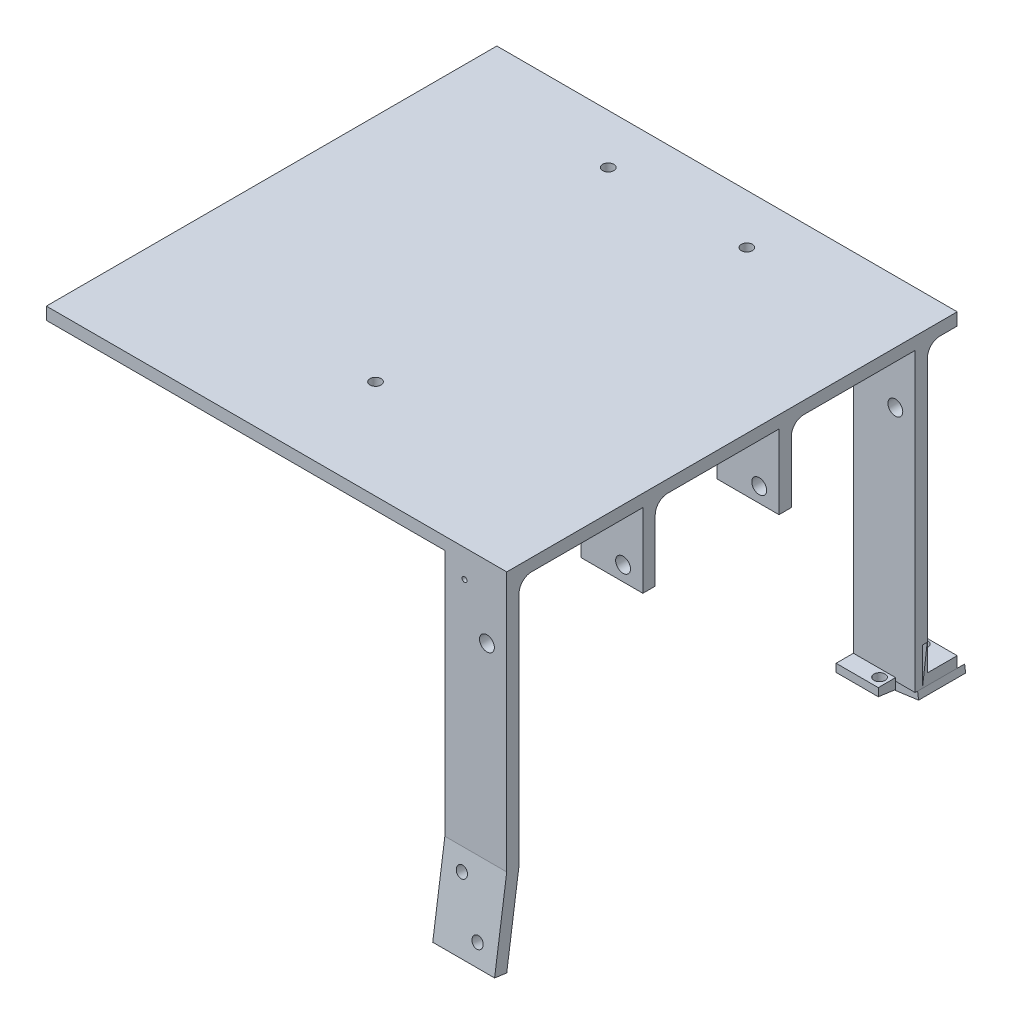
SolidWorks part; units mm, degrees
ref_plane "Front Plane" through (0, 0, 0) normal (0, 0, 1) x (1, 0, 0)
ref_plane "Top Plane" through (0, 0, 0) normal (0, 1, 0) x (1, 0, 0)
ref_plane "Right Plane" through (0, 0, 0) normal (1, 0, 0) x (0, 0, -1)
sketch "Sketch1" plane through (0, 0, 0) normal (0, 1, 0) x (1, 0, 0)
  line L0 (0, 0) -> (0, -300)
  line L1 (0, -300) -> (186, -300)
  line L2 (186, -300) -> (186, 0)
  line L3 (186, 0) -> (176, 0)
  line L4 (176, 0) -> (151, 0)
  line L5 (151, 0) -> (151, -56.1159)
  line L6 (151, -56.1159) -> (35, -56.1159)
  line L7 (35, -56.1159) -> (35, 0)
  line L8 (35, 0) -> (10, 0)
  line L9 (10, 0) -> (0, 0)
  line L10 (93, -300) -> (93, -56.1159) construction
  point P9 (93, -56.1159)
  dimension "D1" = 300
  dimension "D2" = 10
  dimension "D3" = 186
  dimension "D5" = 10
  dimension "D6" = 35
extrude "Boss-Extrude1" add sketch "Sketch1" along normal blind 5
sketch "Sketch2" plane through (0, 0, 0) normal (0, -1, 0) x (1, 0, 0)
  line L1 (50.5, 94) -> (55.5, 94)
  line L2 (50.5, 94) -> (50.5, 71.5)
  line L3 (50.5, 71.5) -> (55.5, 71.5)
  line L4 (55.5, 94) -> (55.5, 71.5)
  line L6 (135.5, 94) -> (130.5, 94)
  line L7 (135.5, 94) -> (135.5, 71.5)
  line L8 (135.5, 71.5) -> (130.5, 71.5)
  line L9 (130.5, 94) -> (130.5, 71.5)
  line L10 (0, 300) -> (186, 300) construction
  line L11 (186, 300) -> (186, 0) construction
  line L12 (0, 0) -> (0, 300) construction
  dimension "D1" = 5
  dimension "D2" = 22.5
  dimension "D3" = 5
  dimension "D4" = 206
  dimension "D5" = 22.5
  dimension "D6" = 50.5
  dimension "D7" = 50.5
extrude "Boss-Extrude2" add sketch "Sketch2" along normal blind 38
sketch "Sketch5" plane through (0, 0, 0) normal (0, -1, 0) x (1, 0, 0)
  line L0 (186, 300) -> (186, 0) construction
  line L1 (186, 295) -> (161, 295)
  line L2 (186, 295) -> (186, 300)
  line L3 (186, 300) -> (161, 300)
  line L4 (161, 295) -> (161, 300)
  line L5 (0, 300) -> (186, 300) construction
  line L6 (186, 240) -> (161, 240)
  line L7 (186, 240) -> (186, 245)
  line L8 (186, 245) -> (161, 245)
  line L9 (161, 240) -> (161, 245)
  line L10 (186, 185) -> (161, 185)
  line L11 (186, 185) -> (186, 190)
  line L12 (186, 190) -> (161, 190)
  line L13 (161, 185) -> (161, 190)
  line L14 (186, 130) -> (161, 130)
  line L15 (186, 130) -> (186, 135)
  line L16 (186, 135) -> (161, 135)
  line L17 (161, 130) -> (161, 135)
  dimension "D1" = 5
  dimension "D2" = 5
  dimension "D3" = 5
  dimension "D4" = 5
  dimension "D5" = 50
  dimension "D6" = 50
  dimension "D7" = 50
  dimension "D8" = 25
extrude "Boss-Extrude3" add sketch "Sketch5" along normal blind 30
fillet "Fillet3" radius 5 4 edges at (173.5, 0, 130) (173.5, 0, 185) (173.5, 0, 240) (173.5, 0, 295)
sketch "Sketch6" plane through (0, 0, 300) normal (0, 0, 1) x (1, 0, 0)
  line L0 (186, -30) -> (161, -30) construction
  line L1 (186, 5) -> (186, -30) construction
  circle A0 centre (178, -24) radius 3
  dimension "D1" = 6
  dimension "D2" = 6
  dimension "D3" = 8
extrude "Cut-Extrude4" cut sketch "Sketch6" against normal blind 172
sketch "Sketch7" plane through (0, 0, 0) normal (0, -1, 0) x (1, 0, 0)
  line L0 (0, 0) -> (0, 300) construction
  line L1 (0, 22.5) -> (5, 22.5)
  line L2 (0, 22.5) -> (0, 0)
  line L3 (0, 0) -> (5, 0)
  line L4 (5, 22.5) -> (5, 0)
  line L5 (186, 125) -> (186, 0) construction
  line L6 (186, 22.5) -> (181, 22.5)
  line L7 (186, 22.5) -> (186, 0)
  line L8 (186, 0) -> (181, 0)
  line L9 (181, 22.5) -> (181, 0)
  line L10 (186, 0) -> (151, 0) construction
  dimension "D1" = 5
  dimension "D2" = 5
  dimension "D3" = 22.5
  dimension "D4" = 22.5
extrude "Boss-Extrude4" add sketch "Sketch7" along normal blind 51.5
sketch "Sketch3" plane through (186, 0, 0) normal (1, 0, 0) x (0, 0, -1)
  line L4 (-71.5, 0) -> (-94, 0)
  line L5 (-71.5, -38) -> (-71.5, 0)
  line L6 (-94, -38) -> (-71.5, -38)
  line L7 (-94, 0) -> (-94, -38)
  line L9 (-71.5, -38) -> (-71.5, 0)
  line L10 (-94, -38) -> (-71.5, -38)
  line L11 (-94, 0) -> (-94, -38)
  line L13 (-71.5, 0) -> (-94, 0)
  circle A0 centre (-74, -32.9) radius 1.3 construction
  circle A1 centre (-91.5, -32.9) radius 1.3 construction
  circle A2 centre (-74, -32.9) radius 1.3
  circle A3 centre (-91.5, -32.9) radius 1.3
  circle A4 centre (-20, -46.4) radius 1.3 construction
  circle A5 centre (-2.5, -46.4) radius 1.3 construction
  circle A6 centre (-20, -46.4) radius 1.3
  circle A7 centre (-2.5, -46.4) radius 1.3
  dimension "D1" = 0
extrude "Cut-Extrude2" cut sketch "Sketch3" against normal through all contours A3 | A2 | A6 | A7
sketch "Sketch9" plane through (0, 0, 0) normal (0, -1, 0) x (1, 0, 0)
  line L0 (35, 0) -> (5, 0) construction
  line L1 (35, 0) -> (151, 0)
  line L2 (35, 0) -> (35, 63.7796)
  line L3 (35, 63.7796) -> (151, 63.7796)
  line L4 (151, 0) -> (151, 63.7796)
  line L5 (35, 56.1159) -> (35, 0) construction
  line L6 (151, 0) -> (151, 56.1159) construction
extrude "Cut-Extrude6" cut sketch "Sketch9" against normal blind 10
sketch "Sketch10" plane through (0, -30, 0) normal (0, -1, 0) x (1, 0, 0)
  line L1 (186, 295) -> (161, 295)
  line L2 (186, 295) -> (186, 300)
  line L3 (186, 300) -> (161, 300)
  line L4 (161, 295) -> (161, 300)
  line L5 (161, 130) -> (186, 130)
  line L6 (161, 130) -> (161, 135)
  line L7 (161, 135) -> (186, 135)
  line L8 (186, 130) -> (186, 135)
extrude "Boss-Extrude5" add sketch "Sketch10" along normal blind 70
sketch "Sketch11" plane through (186, 0, 0) normal (1, 0, 0) x (0, 0, -1)
  line L0 (-300, -100) -> (-304.9019, -134.6439)
  line L1 (-304.9019, -134.6439) -> (-300, -135.3374)
  line L2 (-300, -135.3374) -> (-295, -100)
  line L3 (-300, -100) -> (-295, -100)
extrude "Boss-Extrude6" add sketch "Sketch11" against normal blind 25
sketch "Sketch12" plane through (0, -100, 0) normal (0, -1, 0) x (1, 0, 0)
  line L1 (161, 130) -> (186, 130)
  line L2 (161, 130) -> (161, 135)
  line L3 (161, 135) -> (186, 135)
  line L4 (186, 130) -> (186, 135)
extrude "Boss-Extrude7" add sketch "Sketch12" along normal blind 19.72
sketch "Sketch13" plane through (0, 0, 130) normal (0, 0, -1) x (-1, 0, 0)
  line L0 (-186, -115.3141) -> (-186, -119.72)
  line L1 (-186, -119.72) -> (-186, -5) construction
  line L2 (-186, -119.72) -> (-161, -123.1352)
  line L3 (-161, -123.1352) -> (-161, -115.3141)
  line L4 (-161, -115.3141) -> (-186, -115.3141)
  line L5 (-161, -119.72) -> (-161, -5) construction
  line L8 (-88.5025, -135.5903) -> (-182.3051, -122.7762) construction
extrude "Boss-Extrude8" add sketch "Sketch13" along normal blind 15 and the other way blind 4
sketch "Sketch14" plane through (19.4625, -142.4702, 0) normal (0.1354, -0.9908, 0) x (0.9908, 0.1354, 0)
  line L0 (186.3576, 115) -> (168.0843, 132.0374)
  line L1 (168.0843, 115) -> (142.8521, 115) construction
  line L2 (168.0843, 115) -> (168.0843, 134) construction
  line L3 (168.0843, 132.0374) -> (198.0152, 130.431)
  line L4 (198.0152, 130.431) -> (197.5151, 111.3666)
  line L5 (197.5151, 111.3666) -> (186.3576, 109.6075)
  line L6 (186.3576, 109.6075) -> (186.3576, 115)
extrude "Cut-Extrude7" cut sketch "Sketch14" against normal blind 15
sketch "Sketch15" plane through (0, 39.652, 280.2402) normal (0, 0.1401, 0.9901) x (1, 0, 0)
  line L1 (161, -141.043) -> (161, -176.032) construction
  line L2 (186, -141.043) -> (161, -141.043) construction
  line L3 (186, -141.043) -> (186, -176.032) construction
  line L4 (161, -176.032) -> (186, -176.032) construction
  circle A0 centre (178, -168.032) radius 2.25
  circle A1 centre (169, -149.043) radius 2.25
  dimension "D1" = 4.5
  dimension "D2" = 4.5
  dimension "D3" = 8
  dimension "D4" = 8
  dimension "D5" = 8
  dimension "D6" = 8
extrude "Cut-Extrude8" cut sketch "Sketch15" against normal blind 20
sketch "Sketch16" plane through (0, 0, 0) normal (0, -1, 0) x (1, 0, 0)
  line L1 (166, 272) -> (172, 272)
  line L2 (166, 272) -> (166, 275)
  line L3 (166, 275) -> (172, 275)
  line L4 (172, 272) -> (172, 275)
  line L5 (143.4, 272) -> (137.4, 272)
  line L6 (143.4, 272) -> (143.4, 275)
  line L7 (143.4, 275) -> (137.4, 275)
  line L8 (137.4, 272) -> (137.4, 275)
  line L9 (166, 217) -> (172, 217)
  line L10 (166, 217) -> (166, 220)
  line L11 (166, 220) -> (172, 220)
  line L12 (172, 217) -> (172, 220)
  line L13 (166, 162) -> (172, 162)
  line L14 (166, 162) -> (166, 165)
  line L15 (166, 165) -> (172, 165)
  line L16 (172, 162) -> (172, 165)
  line L17 (137.4, 217) -> (143.4, 217)
  line L18 (137.4, 217) -> (137.4, 220)
  line L19 (137.4, 220) -> (143.4, 220)
  line L20 (143.4, 217) -> (143.4, 220)
  line L21 (137.4, 162) -> (143.4, 162)
  line L22 (137.4, 162) -> (137.4, 165)
  line L23 (137.4, 165) -> (143.4, 165)
  line L24 (143.4, 162) -> (143.4, 165)
  line L25 (186, 180) -> (186, 135) construction
  line L28 (161, 295) -> (186, 295) construction
  line L29 (161, 240) -> (186, 240) construction
  line L30 (161, 185) -> (186, 185) construction
  dimension "D1" = 3
  dimension "D2" = 3
  dimension "D3" = 3
  dimension "D4" = 3
  dimension "D5" = 3
  dimension "D6" = 3
  dimension "D7" = 20
  dimension "D8" = 22.6
  dimension "D9" = 6
  dimension "D10" = 6
  dimension "D11" = 23
  dimension "D12" = 23
  dimension "D13" = 23
extrude "Boss-Extrude9" add sketch "Sketch16" along normal blind 12.4
sketch "Sketch17" plane through (0, 0, 162) normal (0, 0, -1) x (-1, 0, 0)
  arc A0 (-169.75, -6.8) -> (-169.75, -5.6) centre (-168.95, -6.2) ccw construction
  arc A1 (-169.75, -6.8) -> (-169.75, -5.6) centre (-168.95, -6.2) ccw
  circle A2 centre (-168.95, -6.2) radius 1
  circle A3 centre (-140.45, -6.2) radius 1
extrude "Cut-Extrude9" cut sketch "Sketch17" against normal through all contours A1 A2 | A3
sketch "Sketch27" plane through (19.4625, -142.4702, 0) normal (0.1354, -0.9908, 0) x (0.9908, 0.1354, 0)
  line L1 (142.8521, 115) -> (168.0843, 115)
  line L2 (142.8521, 115) -> (142.8521, 134)
  line L3 (142.8521, 134) -> (168.0843, 134)
  line L4 (168.0843, 115) -> (168.0843, 134)
extrude "Boss-Extrude11" add sketch "Sketch27" along normal blind 3
fillet "Fillet4" radius 5 6 edges at (140.4, 0, 275) (169, 0, 275) (140.4, 0, 220) (169, 0, 220) (140.4, 0, 165) (169, 0, 165)
sketch "Sketch18" plane through (0, -115.3141, 0) normal (0, 1, 0) x (1, 0, 0)
  circle A0 centre (174.8857, -120.9947) radius 2.25
  dimension "D1" = 4.5
extrude "Cut-Extrude10" cut sketch "Sketch18" against normal through all
sketch "Sketch19" plane through (0, 0, 0) normal (0, -1, 0) x (1, 0, 0)
  line L0 (42.3, 80.75) -> (39.8, 80.75) construction
  line L1 (39.8, 84.75) -> (39.8, 80.75) construction
  line L2 (42.3, 84.75) -> (42.3, 80.75) construction
  line L3 (39.8, 84.75) -> (42.3, 84.75) construction
  line L4 (42.3, 80.75) -> (39.8, 80.75) construction
  line L5 (39.8, 84.75) -> (39.8, 80.75) construction
  line L6 (42.3, 84.75) -> (42.3, 80.75) construction
  line L7 (39.8, 84.75) -> (42.3, 84.75) construction
  line L8 (143.7, 80.75) -> (143.7, 84.75) construction
  line L9 (143.7, 84.75) -> (146.2, 84.75) construction
  line L10 (146.2, 80.75) -> (146.2, 84.75) construction
  line L11 (146.2, 80.75) -> (143.7, 80.75) construction
  line L12 (143.7, 80.75) -> (143.7, 84.75) construction
  line L13 (143.7, 84.75) -> (146.2, 84.75) construction
  line L14 (146.2, 80.75) -> (146.2, 84.75) construction
  line L15 (146.2, 80.75) -> (143.7, 80.75) construction
  line L16 (43.3, 79.75) -> (38.8, 79.75)
  line L17 (38.8, 85.75) -> (38.8, 79.75)
  line L18 (38.8, 85.75) -> (43.3, 85.75)
  line L19 (43.3, 85.75) -> (43.3, 79.75)
  line L20 (142.7, 79.75) -> (142.7, 85.75)
  line L21 (142.7, 85.75) -> (147.2, 85.75)
  line L22 (147.2, 79.75) -> (147.2, 85.75)
  line L23 (147.2, 79.75) -> (142.7, 79.75)
  line L31 (151, 0) -> (181, 0)
  line L32 (181, 0) -> (181, 22.5)
  line L34 (186, 22.5) -> (186, 125)
  line L35 (186, 125) -> (161, 125)
  line L36 (161, 125) -> (161, 135)
  line L37 (161, 135) -> (186, 135)
  line L38 (186, 135) -> (186, 180)
  line L39 (186, 180) -> (161, 180)
  line L40 (161, 180) -> (161, 190)
  line L41 (161, 190) -> (186, 190)
  line L42 (186, 190) -> (186, 235)
  line L43 (186, 235) -> (161, 235)
  line L44 (161, 235) -> (161, 245)
  line L45 (161, 245) -> (186, 245)
  line L46 (186, 245) -> (186, 290)
  line L47 (186, 290) -> (161, 290)
  line L48 (161, 290) -> (161, 300)
  line L49 (161, 300) -> (0, 300)
  line L50 (0, 300) -> (0, 22.5)
  line L51 (0, 22.5) -> (5, 22.5)
  line L52 (5, 22.5) -> (5, 0)
  line L53 (5, 0) -> (35, 0)
  line L56 (151, 63.7796) -> (151, 0)
  line L57 (151, 63.7796) -> (151, 0)
  line L58 (35, 0) -> (35, 63.7796)
  line L61 (151, 0) -> (181, 0)
  line L64 (186, 22.5) -> (186, 125)
  line L65 (186, 125) -> (161, 125)
  line L66 (161, 125) -> (161, 135)
  line L67 (161, 135) -> (186, 135)
  line L68 (186, 135) -> (186, 180)
  line L69 (186, 180) -> (161, 180)
  line L70 (161, 180) -> (161, 190)
  line L71 (161, 190) -> (186, 190)
  line L72 (186, 190) -> (186, 235)
  line L73 (186, 235) -> (161, 235)
  line L74 (161, 235) -> (161, 245)
  line L75 (161, 245) -> (186, 245)
  line L76 (186, 245) -> (186, 290)
  line L77 (186, 290) -> (161, 290)
  line L78 (161, 290) -> (161, 300)
  line L79 (161, 300) -> (0, 300)
  line L80 (0, 300) -> (0, 22.5)
  line L81 (0, 22.5) -> (5, 22.5)
  line L82 (5, 22.5) -> (5, 0)
  line L83 (5, 0) -> (35, 0)
  line L106 (35, 0) -> (35, 63.7796)
  line L107 (35, 63.7796) -> (151, 63.7796)
  line L108 (35, 63.7796) -> (151, 63.7796)
  line L116 (181, 22.5) -> (186, 22.5)
  line L122 (181, 22.5) -> (186, 22.5)
  line L124 (181, 0) -> (181, 22.5)
  dimension "D1" = 0
  dimension "D2" = 1
  dimension "D3" = 1
extrude "Cut-Extrude12" cut sketch "Sketch19" against normal through all contours L23 L22 L21 L20 | L19 L18 L17 L16
fillet "Fillet6" radius 10 2 edges at (151, 2.5, 63.7796) (35, 2.5, 63.7796)
sketch "Sketch21" plane through (0, 0, 0) normal (0, -1, 0) x (1, 0, 0)
  line L0 (0, 22.5) -> (0, 300) construction
  line L1 (0, 48) -> (27, 48)
  line L2 (0, 48) -> (0, 118)
  line L3 (0, 118) -> (27, 118)
  line L4 (27, 48) -> (27, 118)
  line L5 (186, 125) -> (186, 22.5) construction
  line L6 (186, 48) -> (159, 48)
  line L7 (186, 48) -> (186, 118)
  line L8 (186, 118) -> (159, 118)
  line L9 (159, 48) -> (159, 118)
  line L10 (0, 300) -> (161, 300) construction
  dimension "D1" = 70
  dimension "D2" = 182
  dimension "D3" = 70
  dimension "D4" = 182
  dimension "D5" = 27
  dimension "D6" = 27
extrude "Cut-Extrude14" cut sketch "Sketch21" against normal through all
fillet "Fillet7" radius 10 4 edges at (27, 2.5, 118) (27, 2.5, 48) (159, 2.5, 48) (159, 2.5, 118)
fillet "Fillet8" radius 2.5 2 edges at (55.5, 0, 82.75) (130.5, 0, 82.75)
sketch "Sketch22" plane through (0, 0, 0) normal (0, -1, 0) x (1, 0, 0)
  line L34 (17, 48) -> (0, 48)
  line L35 (0, 48) -> (0, 22.5)
  line L36 (0, 22.5) -> (5, 22.5)
  line L37 (5, 22.5) -> (5, 0)
  line L38 (5, 0) -> (35, 0)
  line L39 (35, 0) -> (35, 53.7796)
  line L40 (45, 63.7796) -> (141, 63.7796)
  line L41 (151, 53.7796) -> (151, 0)
  line L42 (151, 0) -> (181, 0)
  line L43 (181, 0) -> (181, 22.5)
  line L44 (181, 22.5) -> (186, 22.5)
  line L45 (186, 22.5) -> (186, 48)
  line L46 (186, 48) -> (169, 48)
  line L47 (159, 58) -> (159, 108)
  line L48 (169, 118) -> (186, 118)
  line L49 (186, 118) -> (186, 125)
  line L50 (186, 125) -> (161, 125)
  line L51 (161, 125) -> (161, 135)
  line L52 (161, 135) -> (186, 135)
  line L53 (186, 135) -> (186, 180)
  line L54 (186, 180) -> (161, 180)
  line L55 (161, 180) -> (161, 190)
  line L56 (161, 190) -> (186, 190)
  line L57 (186, 190) -> (186, 235)
  line L58 (186, 235) -> (161, 235)
  line L59 (161, 235) -> (161, 245)
  line L60 (161, 245) -> (186, 245)
  line L61 (186, 245) -> (186, 290)
  line L62 (186, 290) -> (161, 290)
  line L63 (161, 290) -> (161, 300)
  line L64 (161, 300) -> (0, 300)
  line L65 (0, 300) -> (0, 118)
  line L66 (0, 118) -> (17, 118)
  line L67 (27, 108) -> (27, 58)
  line L68 (17, 48) -> (0, 48)
  line L69 (0, 48) -> (0, 22.5)
  line L70 (0, 22.5) -> (5, 22.5)
  line L71 (5, 22.5) -> (5, 0)
  line L72 (5, 0) -> (35, 0)
  line L73 (35, 0) -> (35, 53.7796)
  line L74 (45, 63.7796) -> (141, 63.7796)
  line L75 (151, 53.7796) -> (151, 0)
  line L76 (151, 0) -> (181, 0)
  line L77 (181, 0) -> (181, 22.5)
  line L78 (181, 22.5) -> (186, 22.5)
  line L79 (186, 22.5) -> (186, 48)
  line L80 (186, 48) -> (169, 48)
  line L81 (159, 58) -> (159, 108)
  line L82 (169, 118) -> (186, 118)
  line L83 (186, 118) -> (186, 125)
  line L84 (186, 125) -> (161, 125)
  line L85 (161, 125) -> (161, 135)
  line L86 (161, 135) -> (186, 135)
  line L87 (186, 135) -> (186, 180)
  line L88 (186, 180) -> (161, 180)
  line L89 (161, 180) -> (161, 190)
  line L90 (161, 190) -> (186, 190)
  line L91 (186, 190) -> (186, 235)
  line L92 (186, 235) -> (161, 235)
  line L93 (161, 235) -> (161, 245)
  line L94 (161, 245) -> (186, 245)
  line L95 (186, 245) -> (186, 290)
  line L96 (186, 290) -> (161, 290)
  line L97 (161, 290) -> (161, 300)
  line L98 (161, 300) -> (0, 300)
  line L99 (0, 300) -> (0, 118)
  line L100 (0, 118) -> (17, 118)
  line L101 (27, 108) -> (27, 58)
  circle A0 centre (123, 76.0448) radius 2.25 construction
  circle A1 centre (123, 76.0448) radius 2.25
  circle A2 centre (63, 76.0448) radius 2.25 construction
  circle A3 centre (63, 76.0448) radius 2.25
  circle A4 centre (24.5, 25.25) radius 2.25 construction
  circle A5 centre (24.5, 25.25) radius 2.25
  arc A6 (45, 63.7796) -> (35, 53.7796) centre (45, 53.7796) ccw
  arc A7 (151, 53.7796) -> (141, 63.7796) centre (141, 53.7796) ccw
  arc A8 (159, 58) -> (169, 48) centre (169, 58) ccw
  arc A9 (169, 118) -> (159, 108) centre (169, 108) ccw
  arc A10 (27, 108) -> (17, 118) centre (17, 108) ccw
  arc A11 (17, 48) -> (27, 58) centre (17, 58) ccw
  arc A12 (45, 63.7796) -> (35, 53.7796) centre (45, 53.7796) ccw
  arc A13 (151, 53.7796) -> (141, 63.7796) centre (141, 53.7796) ccw
  arc A14 (159, 58) -> (169, 48) centre (169, 58) ccw
  arc A15 (169, 118) -> (159, 108) centre (169, 108) ccw
  arc A16 (27, 108) -> (17, 118) centre (17, 108) ccw
  arc A17 (17, 48) -> (27, 58) centre (17, 58) ccw
  circle A18 centre (161.5, 25.6175) radius 2.25 construction
  circle A19 centre (161.5, 25.6175) radius 2.25
  dimension "D1" = 0
extrude "Cut-Extrude16" cut sketch "Sketch22" against normal blind 10 contours A5 | A3 | A1 | A19
sketch "Sketch23" plane through (0, 0, 135) normal (0, 0, 1) x (1, 0, 0)
  line L1 (178.1063, -118.4368) -> (161.0628, -118.4368)
  line L2 (178.1063, -118.4368) -> (178.1063, -123.5756)
  line L3 (178.1063, -123.5756) -> (161.0628, -123.5756)
  line L4 (161.0628, -118.4368) -> (161.0628, -123.5756)
extrude "Boss-Extrude10" add sketch "Sketch23" along normal blind 7
sketch "Sketch24" plane through (161.0628, 0, 0) normal (-1, 0, 0) x (0, 0, 1)
  line L0 (295, -100) -> (133.6076, -122.8359) construction
  line L1 (142, -121.6484) -> (135, -122.6389)
  line L2 (135, -119.72) -> (135, -123.5756) construction
  line L3 (142, -118.4368) -> (142, -123.5756) construction
  line L4 (142, -121.6484) -> (142, -124.3381)
  line L5 (142, -124.3381) -> (134.715, -124.3381)
  line L6 (134.715, -124.3381) -> (135, -122.6389)
extrude "Cut-Extrude17" cut sketch "Sketch24" against normal up to next
sketch "Sketch25" plane through (0, -118.4368, 0) normal (0, 1, 0) x (1, 0, 0)
  circle A0 centre (174.7191, -138.0894) radius 2.25
  dimension "D1" = 4.5
extrude "Cut-Extrude18" cut sketch "Sketch25" against normal up to next
sketch "Sketch28" plane through (0, 5, 0) normal (0, 1, 0) x (1, 0, 0)
  line L0 (0, -300) -> (186, -300) construction
  circle A0 centre (93, -260) radius 2.25
  point P4 (93, -300)
  dimension "D1" = 4.5
  dimension "D2" = 40
extrude "Cut-Extrude19" cut sketch "Sketch28" against normal through all
sketch "Sketch29" plane through (0, 0, 0) normal (0, -1, 0) x (1, 0, 0)
  line L1 (0, 0) -> (186, 0)
  line L2 (0, 0) -> (0, 118)
  line L3 (0, 118) -> (186, 118)
  line L4 (186, 0) -> (186, 118)
extrude "Cut-Extrude20" cut sketch "Sketch29" against normal blind 10 and the other way blind 126
sketch "Sketch30" plane through (0, 0, 0) normal (0, -1, 0) x (1, 0, 0)
  line L0 (0, 118) -> (0, 300) construction
  line L1 (186, 118) -> (0, 118) construction
  line L2 (186, 180) -> (186, 135) construction
  circle A0 centre (65, 138) radius 2.25
  circle A1 centre (121, 138) radius 2.25
  dimension "D1" = 4.5
  dimension "D2" = 4.5
  dimension "D3" = 65
  dimension "D4" = 20
  dimension "D5" = 20
  dimension "D6" = 65
extrude "Cut-Extrude21" cut sketch "Sketch30" against normal through all
